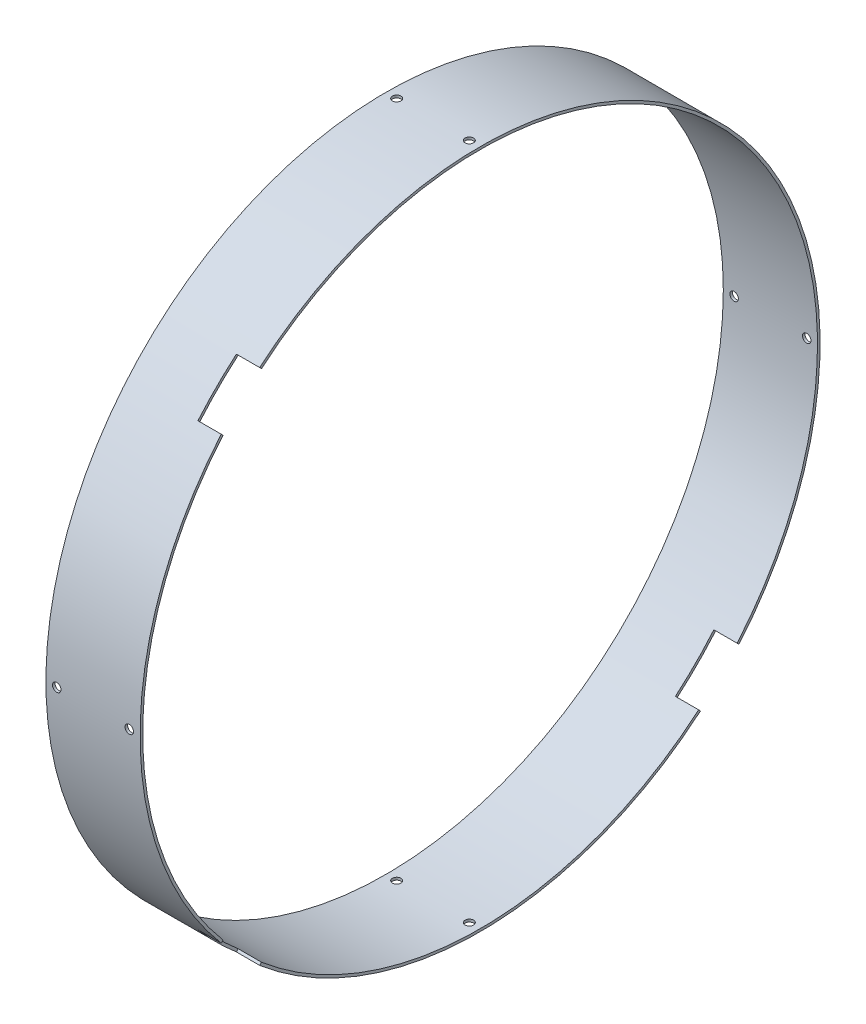
SolidWorks part; units mm, degrees
ref_plane "Front Plane" through (0, 0, 0) normal (0, 0, 1) x (1, 0, 0)
ref_plane "Top Plane" through (0, 0, 0) normal (0, 1, 0) x (1, 0, 0)
ref_plane "Right Plane" through (0, 0, 0) normal (1, 0, 0) x (0, 0, -1)
sketch "Sketch1" plane through (0, 0, 0) normal (1, 0, 0) x (0, 0, -1)
  circle A0 centre (0, 0) radius 100
  circle A1 centre (0, 0) radius 99.238
  dimension "D1" = 200
  dimension "D2" = 0.762
extrude "Boss-Extrude1" add sketch "Sketch1" along normal blind 27.7
ref_plane "Plane1" through (0, 0, 100) normal (0, 0, 1) x (1, 0, 0)
hole_wizard "Ø2.5mm Dowel Hole1" positions "Sketch2" profile "Sketch3" hole size "Ø2.5" standard "ANSI Metric" end condition through all
sketch "Sketch2" plane through (0, 0, 100) normal (0, 0, 1) x (1, 0, 0)
  line L0 (27.7, -100) -> (27.7, 100) construction
  line L1 (0, 100) -> (0, -100) construction
  point P0 (24.525, 0)
  point P2 (3.175, 0)
  dimension "D1" = 3.175
  dimension "D2" = 3.175
sketch "Sketch3" plane through (24.525, 0, 100) normal (1, 0, 0) x (0, -1, 0)
  line L0 (0, 0) -> (0, 200)
  line L1 (0, 200) -> (1.25, 200)
  line L2 (1.25, 200) -> (1.25, 0)
  line L5 (1.25, 0) -> (0, 0)
  line L11 (0, -6.35) -> (0, 107.95) construction
  dimension "Thru Hole Dia." = 2.5
  dimension "Thru Hole Depth" = 200
ref_plane "Plane2" through (0, 100, 0) normal (0, 1, 0) x (1, 0, 0)
hole_wizard "Ø2.5mm Dowel Hole2" positions "Sketch4" profile "Sketch5" hole size "Ø2.5" standard "ANSI Metric" end condition through all
sketch "Sketch4" plane through (0, 100, 0) normal (0, 1, 0) x (1, 0, 0)
  line L0 (27.7, -100) -> (27.7, 100) construction
  line L1 (0, 100) -> (0, -100) construction
  point P0 (24.525, 0)
  point P2 (3.175, 0)
  dimension "D1" = 3.175
  dimension "D2" = 3.175
sketch "Sketch5" plane through (24.525, 100, 0) normal (1, 0, 0) x (0, 0, 1)
  line L0 (0, 0) -> (0, 200)
  line L1 (0, 200) -> (1.25, 200)
  line L2 (1.25, 200) -> (1.25, 0)
  line L5 (1.25, 0) -> (0, 0)
  line L11 (0, -6.35) -> (0, 107.95) construction
  dimension "Thru Hole Dia." = 2.5
  dimension "Thru Hole Depth" = 200
ref_plane "Plane3" through (0, 0, 0) normal (0, 0.7071, -0.7071) x (-1, 0, 0)
sketch "Sketch6" plane through (0, 0, 0) normal (0, 0.7071, -0.7071) x (-1, 0, 0)
  line L0 (-21.35, 7.5) -> (-21.35, -7.5) construction
  line L1 (-21.35, 7.5) -> (-27.7, 7.5) construction
  line L2 (-21.35, -7.5) -> (-27.7, -7.5) construction
  line L3 (-27.7, 7.5) -> (-27.7, -7.5) construction
  line L5 (-27.7, 100) -> (-27.7, -100) construction
  line L6 (-20.85, 8) -> (-28.2, 8)
  line L7 (-28.2, 8) -> (-28.2, -8)
  line L8 (-20.85, -8) -> (-28.2, -8)
  line L9 (-20.85, 8) -> (-20.85, -8)
  point P9 (-27.7, 0)
  dimension "D1" = 15
  dimension "D2" = 6.35
  dimension "D3" = 0.5
extrude "Cut-Extrude1" cut sketch "Sketch6" against normal through all
ref_plane "Plane4" through (0, 0, 0) normal (0, 0.7071, 0.7071) x (-1, 0, 0)
sketch "Sketch7" plane through (0, 0, 0) normal (0, 0.7071, 0.7071) x (-1, 0, 0)
  line L0 (-27.7, 7.5) -> (-27.7, -7.5) construction
  line L1 (-27.7, 7.5) -> (-21.35, 7.5) construction
  line L2 (-27.7, -7.5) -> (-21.35, -7.5) construction
  line L3 (-21.35, 7.5) -> (-21.35, -7.5) construction
  line L4 (-27.7, 99.6795) -> (-27.7, -100) construction
  line L5 (-28.2, 8) -> (-20.85, 8)
  line L6 (-20.85, 8) -> (-20.85, -8)
  line L7 (-28.2, -8) -> (-20.85, -8)
  line L8 (-28.2, 8) -> (-28.2, -8)
  point P6 (-21.35, 0)
  dimension "D1" = 6.35
  dimension "D2" = 15
  dimension "D3" = 0.5
extrude "Cut-Extrude2" cut sketch "Sketch7" against normal through all both and the other way through all
